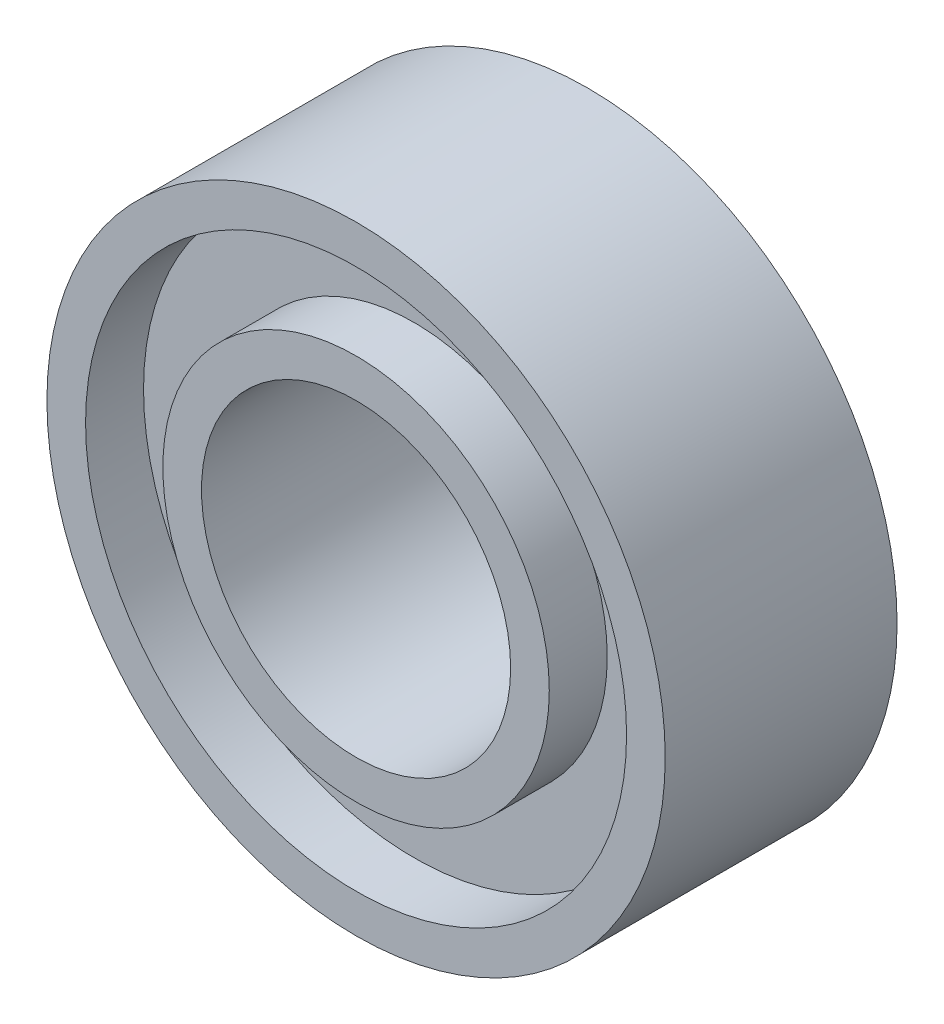
SolidWorks part; units mm, degrees
ref_plane "前视基准面" through (0, 0, 0) normal (0, 0, 1) x (1, 0, 0)
ref_plane "上视基准面" through (0, 0, 0) normal (0, 1, 0) x (1, 0, 0)
ref_plane "右视基准面" through (0, 0, 0) normal (1, 0, 0) x (0, 0, -1)
sketch "草图1" plane through (0, 0, 0) normal (0, 0, 1) x (1, 0, 0)
  circle A0 centre (0, 0) radius 4
  circle A1 centre (0, 0) radius 8
  dimension "D1" = 8
  dimension "D2" = 16
extrude "凸台-拉伸1" add sketch "草图1" along normal blind 6
ref_plane "基准面1" through (0, 0, 3) normal (0, 0, 1) x (1, 0, 0)
sketch "草图2" plane through (0, 0, 6) normal (0, 0, 1) x (1, 0, 0)
  circle A0 centre (0, 0) radius 5
  circle A1 centre (0, 0) radius 7
  dimension "D1" = 10
  dimension "D2" = 14
extrude "切除-拉伸1" cut sketch "草图2" against normal blind 1.5
mirror "镜向1" about plane through (0, 0, 3) normal (0, 0, 1) of "切除-拉伸1"
